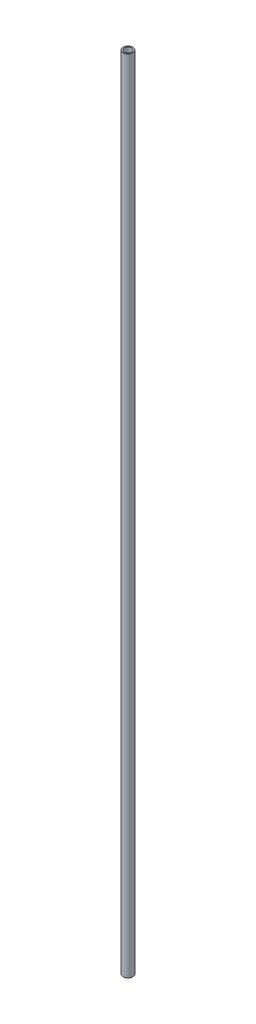
SolidWorks part; units mm, degrees
material "1060-H14"
ref_plane "Front Plane" through (0, 0, 0) normal (0, 0, 1) x (1, 0, 0)
ref_plane "Top Plane" through (0, 0, 0) normal (0, 1, 0) x (1, 0, 0)
ref_plane "Right Plane" through (0, 0, 0) normal (1, 0, 0) x (0, 0, -1)
sketch "Szkic1" plane through (0, 0, 0) normal (0, 1, 0) x (1, 0, 0)
  circle A0 centre (0, 0) radius 4
  circle A1 centre (0, 0) radius 3
  dimension "D1" = 8
  dimension "D2" = 6
extrude "Dodanie-wyciągnięcie1" add sketch "Szkic1" along normal blind 650
